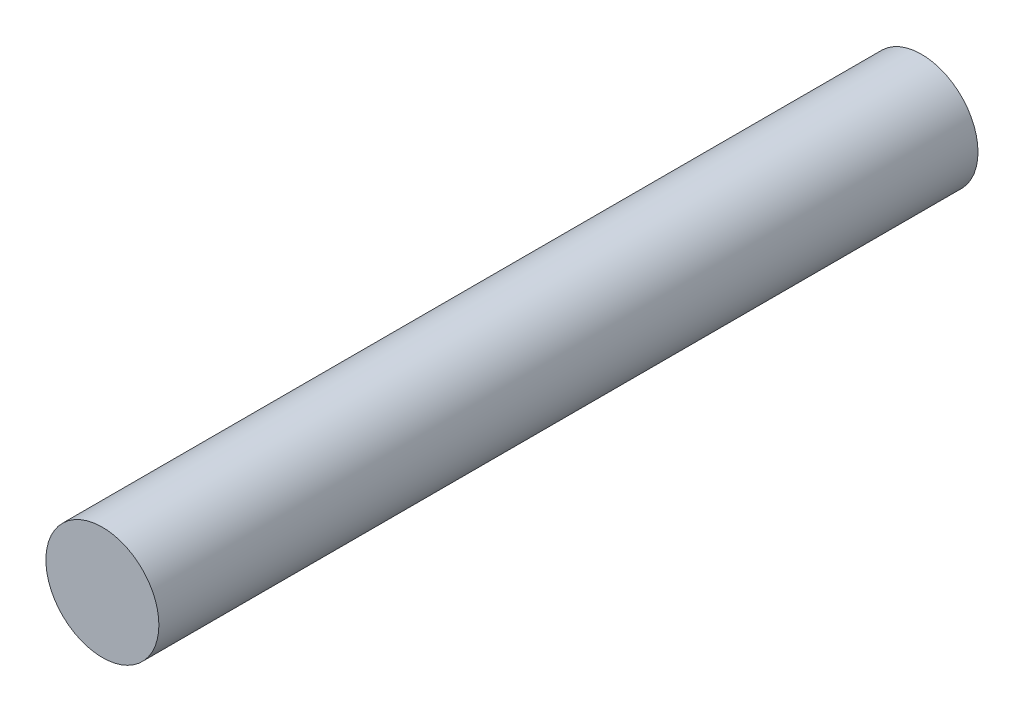
SolidWorks part; units mm, degrees
ref_plane "Спереди" through (0, 0, 0) normal (0, 0, 1) x (1, 0, 0)
ref_plane "Сверху" through (0, 0, 0) normal (0, 1, 0) x (1, 0, 0)
ref_plane "Справа" through (0, 0, 0) normal (1, 0, 0) x (0, 0, -1)
sketch "Эскиз1" plane through (0, 0, 0) normal (0, 0, 1) x (1, 0, 0)
  circle A0 centre (0, 0) radius 10
extrude "Shaft_envelope" add sketch "Эскиз1" along normal blind 145 from offset 72.5
